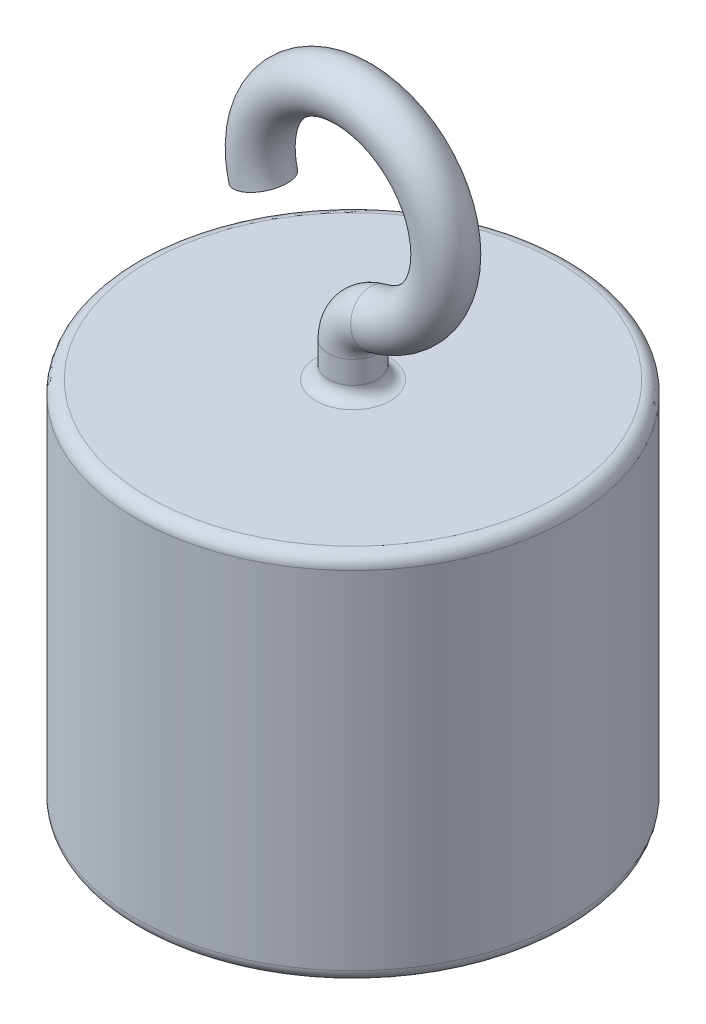
SolidWorks part; units mm, degrees
ref_plane "Front Plane" through (0, 0, 0) normal (0, 0, 1) x (1, 0, 0)
ref_plane "Top Plane" through (0, 0, 0) normal (0, 1, 0) x (1, 0, 0)
ref_plane "Right Plane" through (0, 0, 0) normal (1, 0, 0) x (0, 0, -1)
sketch "Sketch1" plane through (0, 0, 0) normal (0, 0, 1) x (1, 0, 0)
  line L0 (0, 30) -> (0, -30)
  line L2 (35, -30) -> (-35, -30)
  line L3 (35, -30) -> (35, 30)
  line L4 (35, 30) -> (-35, 30)
  line L5 (-35, -30) -> (-35, 30)
  line L6 (35, -30) -> (-35, 30) construction
  line L7 (35, 30) -> (-35, -30) construction
  point P0 (0, 0)
  point P4 (0, 0)
  point P10 (0, 30)
  dimension "D1" = 70
  dimension "D2" = 60
revolve "Revolve1" add sketch "Sketch1" angle 360 about L0
fillet "Fillet1" radius 2 2 edges at (-35, -30, 0) (-35, 30, 0)
sketch "Sketch2" plane through (0, 0, 0) normal (0, 0, 1) x (1, 0, 0)
  line L0 (0, 0) -> (0, 68.9623) construction
  line L1 (0, 30) -> (0, 35.6351)
  line L2 (33, 30) -> (-33, 30) construction
  line L3 (-35.0401, 55) -> (35.0401, 55) construction
  line L4 (0, 55) -> (-32.9248, 46.1778) construction
  arc A0 (0, 35.6351) -> (3.75, 40.4763) centre (5, 35.6351) cw
  arc A1 (3.75, 40.4763) -> (-14.4889, 51.1177) centre (0, 55) ccw
  point P11 (0, 0)
  point P12 (-33.3386, 46.3935)
  point P19 (0, 55)
  dimension "D1" = 5
  dimension "D2" = 15
  dimension "D3" = 15
  dimension "D4" = 25
sketch "Sketch3" plane through (0, 30, 0) normal (0, 1, 0) x (1, 0, 0)
  circle A0 centre (0, 0) radius 4
  dimension "D1" = 8
sweep "Sweep1" add profiles "Sketch3" path "Sketch2"
fillet "Fillet2" radius 2 1 edges at (-4, 30, 0)
sketch "Sketch4" plane through (0, 0, 0) normal (1, 0, 0) x (0, 0, -1)
  line L0 (0, -30) -> (0, 79.0627) construction
  line L1 (-33, -30) -> (33, -30) construction
  line L2 (-3, -24) -> (-3, -20)
  line L3 (-20, -30) -> (0, -30)
  line L4 (-20, -30) -> (-20, -24)
  line L5 (-20, -24) -> (0, -24)
  line L6 (0, -30) -> (0, -24)
  line L7 (-3, -20) -> (0, -20)
  line L8 (0, -20) -> (0, -24)
  dimension "D1" = 20
  dimension "D2" = 6
  dimension "D3" = 10
  dimension "D4" = 3
revolve "Cut-Revolve1" cut sketch "Sketch4" angle 360 about L0
